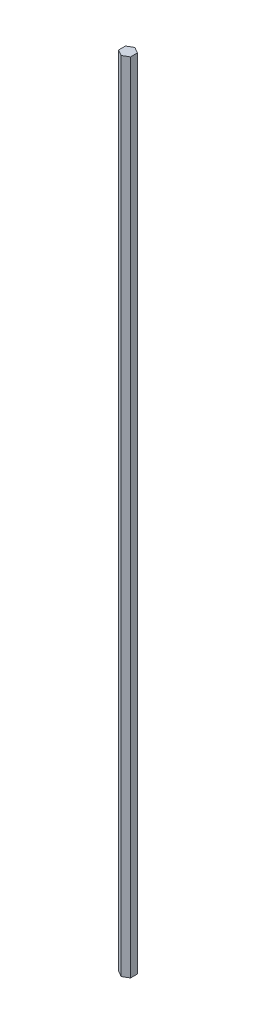
SolidWorks part; units mm, degrees
ref_plane "Front Plane" through (0, 0, 0) normal (0, 0, 1) x (1, 0, 0)
ref_plane "Top Plane" through (0, 0, 0) normal (0, 1, 0) x (1, 0, 0)
ref_plane "Right Plane" through (0, 0, 0) normal (1, 0, 0) x (0, 0, -1)
sketch "Sketch1" plane through (0, 0, 0) normal (0, 1, 0) x (1, 0, 0)
  line L1 (0, 8.6603) -> (-7.5, 4.3301)
  line L2 (-7.5, 4.3301) -> (-7.5, -4.3301)
  line L3 (-7.5, -4.3301) -> (0, -8.6603)
  line L4 (0, -8.6603) -> (7.5, -4.3301)
  line L5 (7.5, -4.3301) -> (7.5, 4.3301)
  line L6 (7.5, 4.3301) -> (0, 8.6603)
  circle A0 centre (0, 0) radius 7.5 construction
  dimension "D1" = 15
extrude "Boss-Extrude1" add sketch "Sketch1" along normal blind 1000
